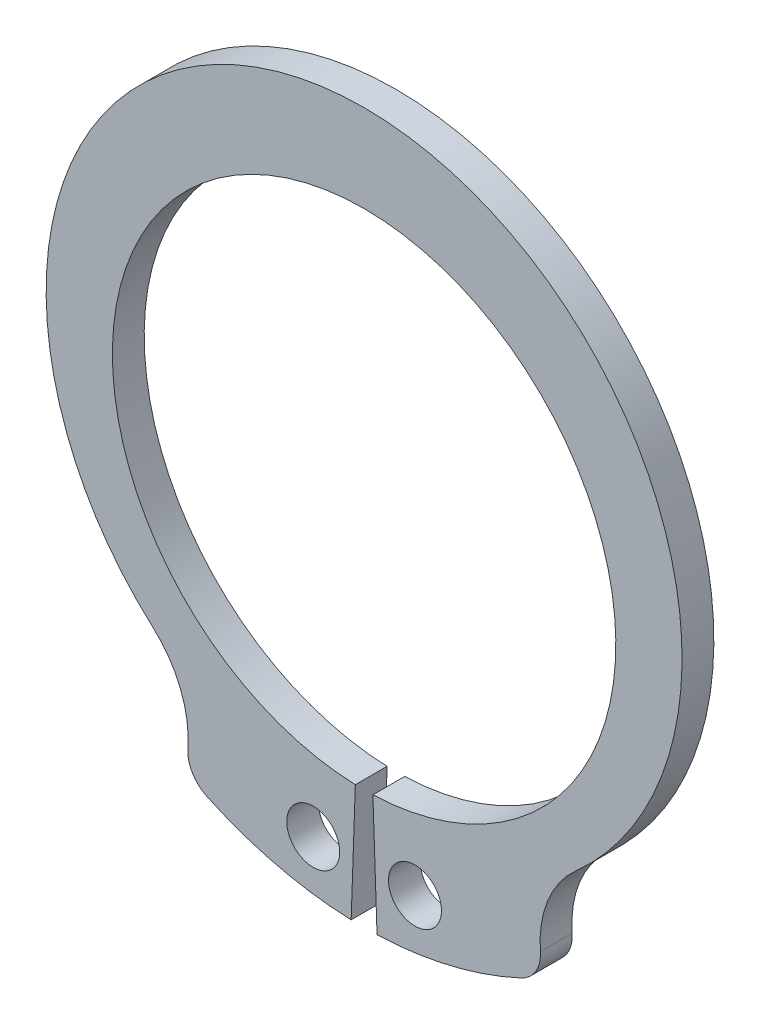
SolidWorks part; units mm, degrees
ref_plane "Front Plane" through (0, 0, 0) normal (0, 0, 1) x (1, 0, 0)
ref_plane "Top Plane" through (0, 0, 0) normal (0, 1, 0) x (1, 0, 0)
ref_plane "Right Plane" through (0, 0, 0) normal (1, 0, 0) x (0, 0, -1)
sketch "Sketch2" plane through (0, 0, 0) normal (0, 0, 1) x (1, 0, 0)
  line L0 (0, 0) -> (0, -23.75) construction
  line L1 (0, 0) -> (6.5464, -22.83)
  line L2 (0, 0) -> (-6.5464, -22.83)
  circle A0 centre (0, 0) radius 23.75
  circle A1 centre (0, -1.4) radius 20.75
  circle A6 centre (-7.7551, -17.9755) radius 2.5
  circle A7 centre (-11.896, -11.7222) radius 5
  circle A9 centre (0, -1.4) radius 15.8
  circle A10 centre (-7.7551, -17.9755) radius 1
  circle A11 centre (7.7551, -17.9755) radius 1
  circle A12 centre (7.7551, -17.9755) radius 2.5
  circle A13 centre (11.896, -11.7222) radius 5
  dimension "D1" = 47.5
  dimension "D5" = 41.5
  dimension "D2" = 10
  dimension "D6" = 5
  dimension "D7" = 31.6
  dimension "D8" = 2
  dimension "D3" = 32
  dimension "D4" = 1.4
sketch "Sketch3" plane through (0, 0, 0) normal (0, 0, 1) x (1, 0, 0)
  line L0 (0, 0) -> (0, -16.3969) construction
  line L1 (0, 0) -> (0.4886, -13.9915)
  line L2 (0, 0) -> (-0.4886, -13.9915)
  circle A0 centre (0, 0) radius 9.5
  circle A1 centre (0, 0) radius 14
  circle A2 centre (0, 0.8) radius 12
  circle A3 centre (10.6411, -11.1485) radius 4
  circle A4 centre (5.4063, -11.5471) radius 1.25
  circle A5 centre (1.9197, -11.9915) radius 1
  circle A6 centre (-10.6411, -11.1485) radius 4
  circle A7 centre (-5.4063, -11.5471) radius 1.25
  circle A8 centre (-1.9197, -11.9915) radius 1
  dimension "D1" = 19
  dimension "D2" = 24
  dimension "D3" = 0.8
  dimension "D4" = 28
  dimension "D7" = 2.5
  dimension "D8" = 8
  dimension "D11" = 2
  dimension "D5" = 2
  dimension "D6" = 5
  dimension "D9" = 1.5
  dimension "D10" = 2
extrude "Boss-Extrude1" add sketch "Sketch3" along normal blind 1.2 contours A2 A8 L2 A0 L1 A5 | A2 A8 A6 A7 A1 L2 | A7 | A5 A2 L1 A1 A4 A3 | A4
equation "\"D1@Sketch2\" = \"G_anneau_alesage_rouleau\""
equation "\"c_anneau\"=31.6"
equation "\"D5@Sketch2\" = \"G_anneau_alesage_rouleau\" - 6"
equation "\"e_anneau\"=1.75"
equation "\"D2@Sketch2\"=2*\"D6@Sketch2\""
equation "\"D7@Sketch2\"=\"c_anneau\""
equation "\"d_ext_rouleau\"= 90"
equation "\"epaisseur_rouleau\"=80"
equation "\"alesage-rouleau\"= 52"
equation "\"jeu_dent_rouleau\"= 2"
equation "\"profondeur_dent_rouleau\"=4"
equation "\"n_dent_roueau\"= 15"
equation "\"d_ext_roulement_rouleau\"= 42"
equation "\"d_int_roulement_rouleau\"= 20"
equation "\"B_roulement_rouleau\"= 12"
equation "\"r_roulement_rouleau\"= 0.6"
equation "\"d_bille_roulement_rouleau\"= 8"
equation "\"F_anneau_alesage_rouleau\"=1.85"
equation "\"G_anneau_alesage_rouleau\"=47.5"
equation "\"K_anneau_alesage_rouleau\"=3.75"
equation "\"d_vis_flasque_rouleau\"=5"
equation "\"l-x_vis_flasque_rouleau\"=4"
equation "\"g_anneau_arbre_rouleau\"=19"
equation "\"f_anneau_arbre_rouleau\"=1.3"
equation "\"k_anneau_arbre_rouleau\"=1.5"
equation "\"h_matrice\"= 22"
equation "\"d_matrice\"= 220"
equation "\"d_granulat\"= 8"
equation "\"zone_vide_matrice\" = 48"
equation "\"d_alesage_matrice\"=20"
equation "\"a_clavette_alesage_matrice\"=6"
equation "\"entrax_vis_rouleau\"=65"
